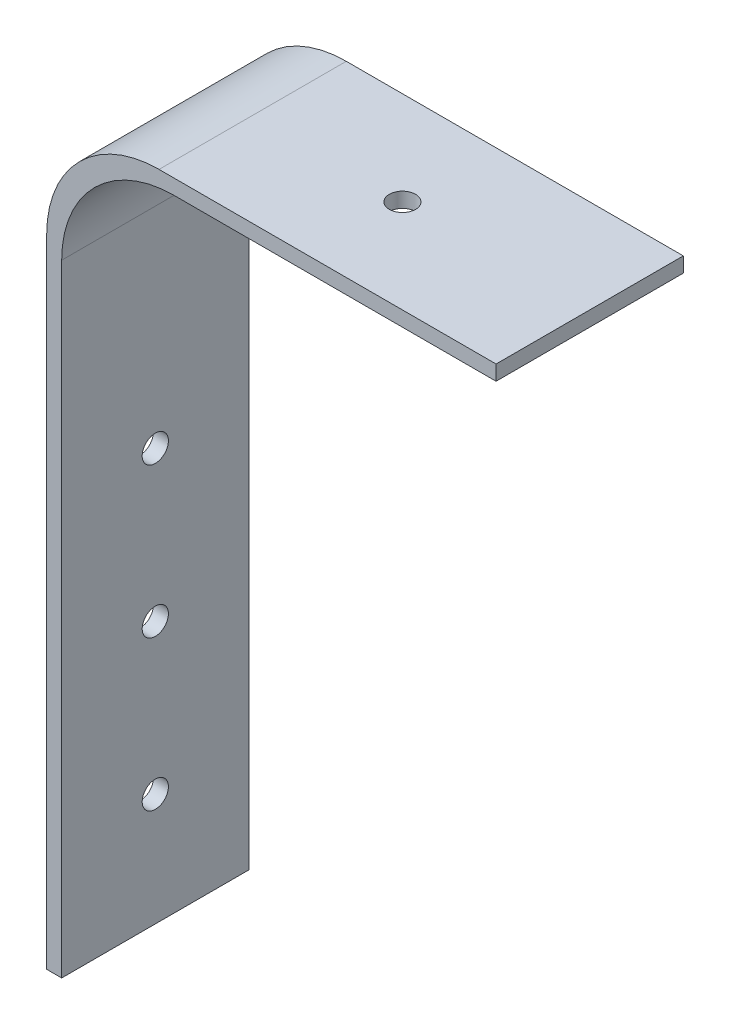
SolidWorks part; units mm, degrees
ref_plane "Front Plane" through (0, 0, 0) normal (0, 0, 1) x (1, 0, 0)
ref_plane "Top Plane" through (0, 0, 0) normal (0, 1, 0) x (1, 0, 0)
ref_plane "Right Plane" through (0, 0, 0) normal (1, 0, 0) x (0, 0, -1)
sketch "Sketch1" plane through (0, 0, 0) normal (0, 0, 1) x (1, 0, 0)
  line L0 (-15, 30) -> (30, 30)
  line L1 (-30, 15) -> (-30, -70)
  line L2 (-30, -70) -> (-28, -70)
  line L3 (-28, -70) -> (-28, 13)
  line L4 (30, 30) -> (30, 28)
  line L5 (30, 28) -> (-13, 28)
  line L6 (55, 0) -> (-55, 0) construction
  line L7 (0, -55) -> (0, 55) construction
  arc A0 (-13, 28) -> (-28, 13) centre (-13, 13) ccw
  arc A1 (-15, 30) -> (-30, 15) centre (-15, 15) ccw
  point P14 (-30, 30)
  dimension "D7" = 15
  dimension "D8" = 15
  dimension "D1" = 60
  dimension "D2" = 100
  dimension "D3" = 2
  dimension "D4" = 2
  dimension "D5" = 30
  dimension "D6" = 30
extrude "Boss-Extrude1" add sketch "Sketch1" along normal blind 25
sketch "Sketch2" plane through (-30, 0, 0) normal (-1, 0, 0) x (0, 0, 1)
  line L0 (25, 15) -> (25, -70) construction
  line L2 (13.75, 0) -> (-13.75, 0) construction
  circle A0 centre (12.5, -15) radius 1.75
  circle A1 centre (12.5, -35) radius 1.75
  circle A2 centre (12.5, -55) radius 1.75
  dimension "D2" = 3.5
  dimension "D1" = 12.5
  dimension "D3" = 15
  dimension "D5" = 20
  dimension "D4" = 3
extrude "Cut-Extrude1" cut sketch "Sketch2" against normal blind 2
sketch "Sketch3" plane through (0, 30, 0) normal (0, 1, 0) x (1, 0, 0)
  line L0 (30, -25) -> (-15, -25) construction
  line L1 (30, -25) -> (30, 0) construction
  circle A0 centre (5, -12.5) radius 1.75
  dimension "D1" = 3.5
  dimension "D2" = 12.5
  dimension "D3" = 25
extrude "Cut-Extrude2" cut sketch "Sketch3" against normal blind 2
